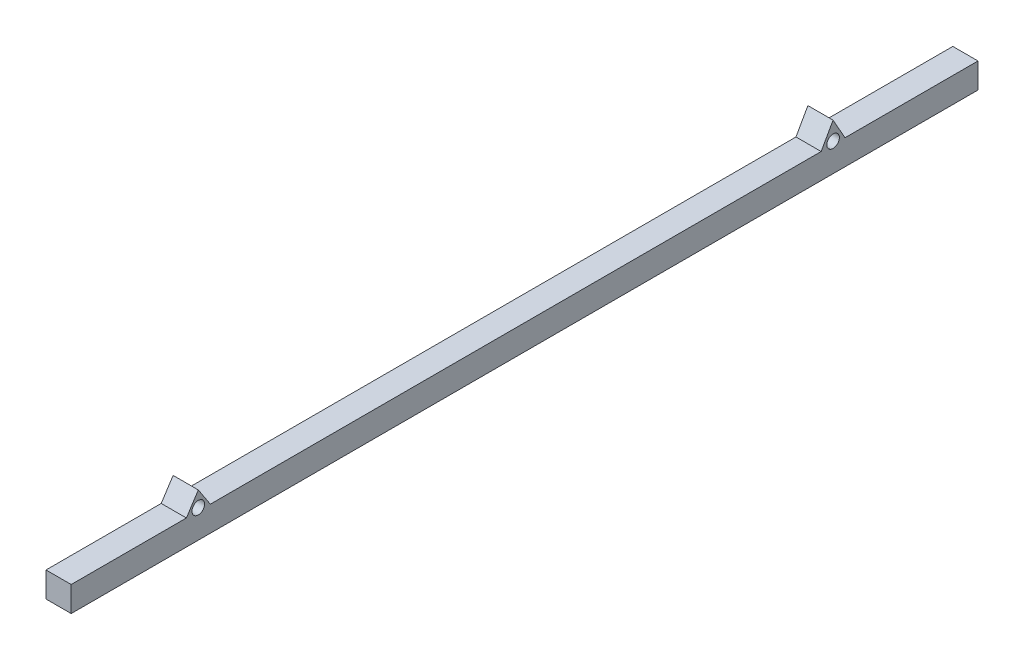
SolidWorks part; units mm, degrees
material "6061 Alloy"
ref_plane "Ground" through (0, 0, 0) normal (0, 0, 1) x (1, 0, 0)
ref_plane "Right" through (0, 0, 0) normal (0, 1, 0) x (1, 0, 0)
ref_plane "Front" through (0, 0, 0) normal (1, 0, 0) x (0, 0, -1)
sketch "Sketch1" plane through (0, 0, 0) normal (1, 0, 0) x (0, 0, -1)
  line L0 (25.233, 8.6385) -> (22.8699, 5)
  line L1 (0, 0) -> (180, 0)
  line L2 (0, 0) -> (0, 5)
  line L4 (180, 0) -> (180, 5)
  line L13 (25.233, 8.6385) -> (27.6222, 5)
  line L14 (151.233, 9.2119) -> (148.8665, 5)
  line L16 (151.233, 9.2119) -> (153.597, 5)
  line L17 (153.597, 5) -> (180, 5)
  line L18 (27.6222, 5) -> (148.8665, 5)
  line L19 (0, 5) -> (22.8699, 5)
  circle A0 centre (25.233, 5.5938) radius 1.25
  circle A1 centre (151.233, 5.5938) radius 1.25
  dimension "D4" = 28.767
  dimension "D5" = 2.5
  dimension "D1" = 5
  dimension "D2" = 126
  dimension "D3" = 180
extrude "Boss-Extrude1" add sketch "Sketch1" against normal blind 5
